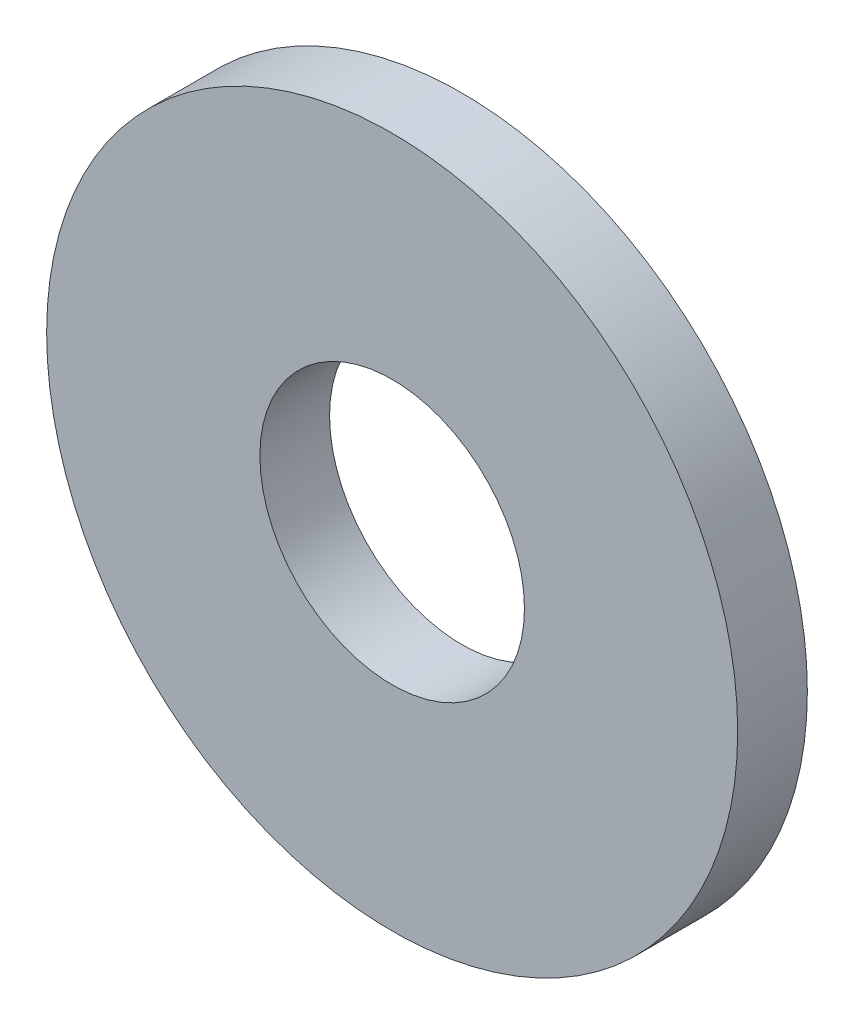
SolidWorks part; units mm, degrees
ref_plane "Front Plane" through (0, 0, 0) normal (0, 0, 1) x (1, 0, 0)
ref_plane "Top Plane" through (0, 0, 0) normal (0, 1, 0) x (1, 0, 0)
ref_plane "Right Plane" through (0, 0, 0) normal (1, 0, 0) x (0, 0, -1)
sketch "Sketch1" plane through (0, 0, 0) normal (0, 0, 1) x (1, 0, 0)
  circle A0 centre (0, 0) radius 9.3218
  circle A1 centre (0, 0) radius 3.5687
  point P5 (0, -9.3218)
  dimension "OD" = 18.6436
  dimension "ID" = 7.1374
sketch "Sketch2" plane through (0, 0, 0) normal (1, 0, 0) x (0, 0, -1)
  line L0 (-0.9398, 0) -> (0.9398, 0) construction
  point P0 (-0.9398, -9.3218)
  point P4 (0, 0)
  point P6 (0.9398, -9.3218)
  dimension "Thickness Range" = 1.8796
sketch "Sketch3" plane through (0, 0, 0) normal (0, 0, 1) x (1, 0, 0)
  circle A0 centre (0, 0) radius 9.3218 construction
  circle A1 centre (0, 0) radius 3.5687 construction
  circle A2 centre (0, 0) radius 9.3218
  circle A3 centre (0, 0) radius 3.5687
extrude "Boss-Extrude1" add sketch "Sketch3" along normal up to vertex (0.9398 mm away) and the other way up to vertex (0.9398 mm away) up to point (0, -9.3218, 0.9398) other way up to point (0, -9.3218, -0.9398)
